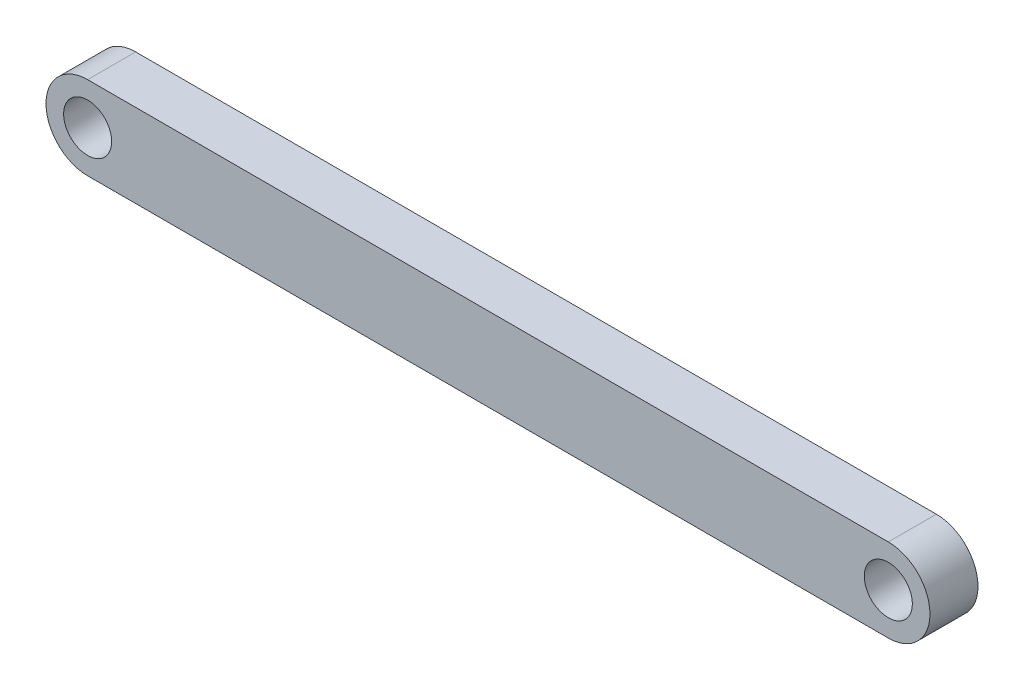
SolidWorks part; units mm, degrees
ref_plane "Front Plane" through (0, 0, 0) normal (0, 0, 1) x (1, 0, 0)
ref_plane "Top Plane" through (0, 0, 0) normal (0, 1, 0) x (1, 0, 0)
ref_plane "Right Plane" through (0, 0, 0) normal (1, 0, 0) x (0, 0, -1)
sketch "Sketch1" plane through (0, 0, 0) normal (0, 0, 1) x (1, 0, 0)
  line L0 (-125, 0) -> (125, 0) construction
  line L1 (-125, 13) -> (125, 13)
  line L2 (-125, -13) -> (125, -13)
  circle A0 centre (-125, 0) radius 7.5
  circle A1 centre (-125, 0) radius 7.5
  arc A2 (-125, 13) -> (-125, -13) centre (-125, 0) ccw
  arc A3 (125, -13) -> (125, 13) centre (125, 0) ccw
  circle A4 centre (125, 0) radius 7.5
  point P3 (0, 0)
  dimension "D3" = 15
  dimension "D1" = 250
  dimension "D2" = 13
extrude "Boss-Extrude1" add sketch "Sketch1" against normal blind 15
